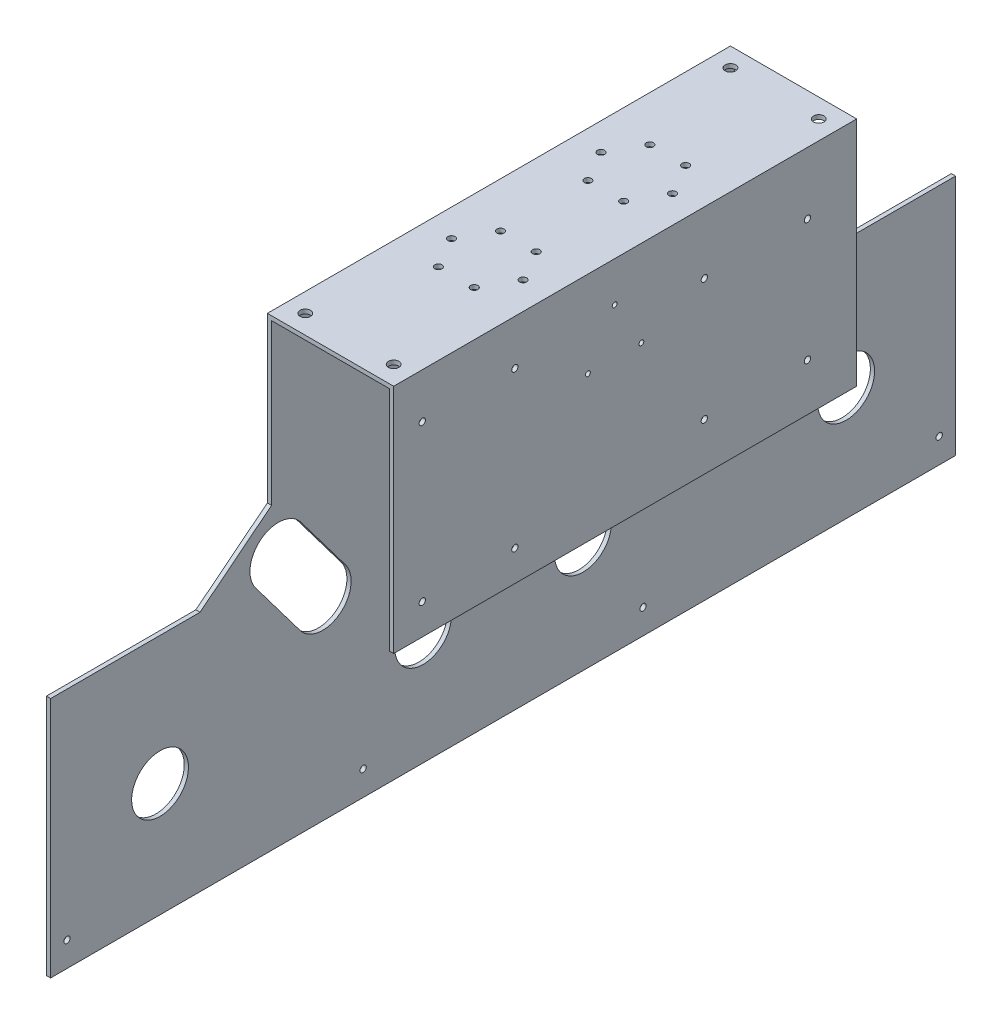
SolidWorks part; units mm, degrees
ref_plane "Front Plane" through (0, 0, 0) normal (0, 0, 1) x (1, 0, 0)
ref_plane "Top Plane" through (0, 0, 0) normal (0, 1, 0) x (1, 0, 0)
ref_plane "Right Plane" through (0, 0, 0) normal (1, 0, 0) x (0, 0, -1)
sketch "Sketch1" plane through (0, 0, 0) normal (0, 0, 1) x (1, 0, 0)
  line L1 (-58, -2) -> (-2, -2)
  line L2 (-2, -2) -> (-2, -110)
  line L6 (0, -110) -> (0, 0)
  line L7 (0, 0) -> (-60, 0)
  line L8 (-2, -110) -> (0, -110)
  line L9 (-60, 0) -> (-60, -220)
  line L10 (-60, -220) -> (-58, -220)
  line L11 (-58, -220) -> (-58, -2)
  dimension "D1" = 60
  dimension "D2" = 2
  dimension "D3" = 2
  dimension "D4" = 110
  dimension "D5" = 220
  dimension "D6" = 2
extrude "Boss-Extrude1" add sketch "Sketch1" along normal blind 220
sketch "Sketch2" plane through (0, 0, 0) normal (0, 1, 0) x (1, 0, 0)
  line L0 (-60, -110) -> (0, -110) construction
  line L2 (-30, -128.5) -> (-30, -162.5) construction
  line L3 (-47, -74.5) -> (-30, -74.5) construction
  line L4 (-47, -145.5) -> (-30, -145.5) construction
  line L5 (-30, -74.5) -> (-47, -74.5) construction
  line L6 (-30, -145.5) -> (-47, -145.5) construction
  line L7 (-30, -74.5) -> (-30, -91.5) construction
  line L9 (-30, -74.5) -> (-42.5, -62.5) construction
  line L10 (-60, -220) -> (-60, 0) construction
  line L11 (0, -220) -> (0, 0) construction
  circle A0 centre (-30, -74.5) radius 17 construction
  circle A1 centre (-30, -145.5) radius 17 construction
  circle A2 centre (-47, -74.5) radius 1.7
  circle A3 centre (-47, -74.5) radius 3
  circle A4 centre (-47, -145.5) radius 1.7
  circle A5 centre (-47, -145.5) radius 3
  circle A6 centre (-38.5, -59.7776) radius 3
  circle A7 centre (-38.5, -59.7776) radius 1.7
  circle A8 centre (-21.5, -59.7776) radius 3
  circle A9 centre (-21.5, -59.7776) radius 1.7
  circle A10 centre (-13, -74.5) radius 3
  circle A11 centre (-13, -74.5) radius 1.7
  circle A12 centre (-21.5, -89.2224) radius 3
  circle A13 centre (-21.5, -89.2224) radius 1.7
  circle A14 centre (-38.5, -89.2224) radius 3
  circle A15 centre (-38.5, -89.2224) radius 1.7
  circle A16 centre (-38.5, -130.7776) radius 1.7
  circle A17 centre (-38.5, -130.7776) radius 3
  circle A18 centre (-21.5, -130.7776) radius 1.7
  circle A19 centre (-21.5, -130.7776) radius 3
  circle A20 centre (-13, -145.5) radius 1.7
  circle A21 centre (-13, -145.5) radius 3
  circle A22 centre (-21.5, -160.2224) radius 1.7
  circle A23 centre (-21.5, -160.2224) radius 3
  circle A24 centre (-38.5, -160.2224) radius 1.7
  circle A25 centre (-38.5, -160.2224) radius 3
  dimension "D2" = 34
  dimension "D3" = 6
  dimension "D4" = 3.4
  dimension "D5" = 3.4
  dimension "D6" = 6
  dimension "D1" = 71
  dimension "D9" = 17
  dimension "D11" = 17
  dimension "D8" = 6
  dimension "D10" = 6
extrude "Cut-Extrude2" cut sketch "Sketch2" against normal up to surface (2 mm away) contours A7 | A9 | A11 | A13 | A15 | A2 | A16 | A4 | A24 | A22 | A20 | A18 up to face at (-30, -2, 110)
sketch "Sketch3" plane through (0, 0, 0) normal (1, 0, 0) x (0, 0, -1)
  line L0 (-127.7, -40.9985) -> (-102.3, -40.9985) construction
  line L1 (-102.3, -40.9985) -> (-115, -19.0015) construction
  line L2 (-115, -19.0015) -> (-127.7, -40.9985) construction
  line L3 (-127.7, -40.9985) -> (-115, -40.9985) construction
  line L4 (-115, -40.9985) -> (-115, -19.0015) construction
  line L13 (-121.35, -30) -> (-108.65, -30) construction
  circle A0 centre (-115, -19.0015) radius 1.15
  circle A1 centre (-127.7, -40.9985) radius 1.15
  circle A2 centre (-102.3, -40.9985) radius 1.15
  dimension "D1" = 2.3
  dimension "D2" = 2.3
  dimension "D3" = 2.3
  dimension "D4" = 25.4
  dimension "D5" = 25.4
  dimension "D6" = 25.4
  dimension "D7" = 115
  dimension "D8" = 30
extrude "Cut-Extrude4" cut sketch "Sketch3" against normal blind 10
sketch "Sketch4" plane through (0, 0, 0) normal (1, 0, 0) x (0, 0, -1)
  line L0 (-206.3978, -21.4333) -> (-162.3978, -21.4333) construction
  line L1 (-162.3978, -21.4333) -> (-162.3978, -95.4333) construction
  line L2 (-162.3978, -95.4333) -> (-206.3978, -95.4333) construction
  line L3 (-206.3978, -95.4333) -> (-206.3978, -21.4333) construction
  line L4 (-72.3978, -29.4333) -> (-23.3978, -29.4333) construction
  line L5 (-23.3978, -29.4333) -> (-23.3978, -87.4333) construction
  line L6 (-72.3978, -87.4333) -> (-72.3978, -29.4333) construction
  line L7 (-72.3978, -87.4333) -> (-23.3978, -87.4333) construction
  circle A0 centre (-206.3978, -21.4333) radius 1.5
  circle A1 centre (-162.3978, -21.4333) radius 1.5
  circle A2 centre (-206.3978, -95.4333) radius 1.5
  circle A3 centre (-162.3978, -95.4333) radius 1.5
  circle A4 centre (-72.3978, -29.4333) radius 1.5
  circle A5 centre (-23.3978, -29.4333) radius 1.5
  circle A6 centre (-72.3978, -87.4333) radius 1.5
  circle A7 centre (-23.3978, -87.4333) radius 1.5
  dimension "D1" = 3
  dimension "D2" = 3
  dimension "D3" = 3
  dimension "D4" = 3
  dimension "D9" = 3
  dimension "D10" = 3
  dimension "D11" = 3
  dimension "D12" = 3
  dimension "D5" = 74
  dimension "D6" = 44
  dimension "D7" = 40
  dimension "D8" = 37
  dimension "D13" = 58
  dimension "D14" = 49
  dimension "D15" = 29
  dimension "D16" = 50
extrude "Cut-Extrude5" cut sketch "Sketch4" against normal blind 10
sketch "Sketch6" plane through (-60, 0, 0) normal (-1, 0, 0) x (0, 0, 1)
  line L0 (0, -78) -> (-34, -105)
  line L1 (0, 0) -> (0, -220) construction
  line L2 (-34, -105) -> (-105, -105)
  line L3 (-105, -105) -> (-105, -220)
  line L4 (-105, -220) -> (0, -220)
  line L5 (110, 0) -> (110, -220) construction
  line L6 (220, 0) -> (0, 0) construction
  line L7 (220, -220) -> (0, -220) construction
  line L8 (0, -78) -> (0, -220)
  line L9 (220, -78) -> (220, -220)
  line L10 (325, -220) -> (220, -220)
  line L11 (325, -105) -> (325, -220)
  line L12 (254, -105) -> (325, -105)
  line L13 (220, -78) -> (254, -105)
  dimension "D1" = 34
  dimension "D2" = 105
  dimension "D3" = 27
  dimension "D4" = 105
extrude "Boss-Extrude2" add sketch "Sketch6" against normal blind 2
sketch "Sketch8" plane through (-60, 0, 0) normal (-1, 0, 0) x (0, 0, 1)
  line L0 (-7.5632, -108.249) -> (13.5004, -136.2012)
  line L1 (14, -92) -> (35.0635, -119.9522)
  line L2 (3.2184, -100.1245) -> (24.2819, -128.0767) construction
  line L3 (-34, -105) -> (-105, -105) construction
  line L4 (-105, -105) -> (-105, -220) construction
  line L5 (325, -220) -> (-105, -220) construction
  line L6 (110, 0) -> (110, -220) construction
  line L7 (220, 0) -> (0, 0) construction
  line L8 (-53, -166) -> (72, -166) construction
  line L9 (206, -92) -> (184.9365, -119.9522)
  line L10 (227.5632, -108.249) -> (206.4996, -136.2012)
  line L11 (-97.2, -208.2) -> (43.5, -208.2) construction
  arc A0 (14, -92) -> (-7.5632, -108.249) centre (3.2184, -100.1245) ccw
  arc A1 (13.5004, -136.2012) -> (35.0635, -119.9522) centre (24.2819, -128.0767) ccw
  circle A2 centre (-53, -166) radius 13.5
  circle A3 centre (72, -166) radius 13.5
  circle A4 centre (148, -166) radius 13.5
  arc A5 (206, -92) -> (227.5632, -108.249) centre (216.7816, -100.1245) cw
  arc A6 (206.4996, -136.2012) -> (184.9365, -119.9522) centre (195.7181, -128.0767) cw
  circle A7 centre (273, -166) radius 13.5
  circle A8 centre (-97.2, -208.2) radius 1.5
  circle A9 centre (43.5, -208.2) radius 1.5
  circle A10 centre (176.5, -208.2) radius 1.5
  circle A11 centre (317.2, -208.2) radius 1.5
  circle A12 centre (71.99, -66.8) radius 13.5
  circle A13 centre (148.01, -66.8) radius 13.5
  dimension "D1" = 27
  dimension "D2" = 27
  dimension "D4" = 14
  dimension "D7" = 27
  dimension "D8" = 27
  dimension "D12" = 3
  dimension "D13" = 3
  dimension "D17" = 27
  dimension "D3" = 35
  dimension "D5" = 14
  dimension "D6" = 53
  dimension "D9" = 52
  dimension "D10" = 54
  dimension "D11" = 38
  dimension "D14" = 7.8
  dimension "D15" = 148.5
  dimension "D16" = 11.8
  dimension "D18" = 38.01
  dimension "D19" = 66.8
extrude "Cut-Extrude6" cut sketch "Sketch8" against normal blind 2
sketch "Sketch9" plane through (0, 0, 0) normal (0, 1, 0) x (1, 0, 0)
  line L0 (-60, -220) -> (-60, 0) construction
  line L1 (0, 0) -> (-60, 0) construction
  line L2 (0, -220) -> (0, 0) construction
  line L3 (-60, -110) -> (0, -110) construction
  circle A0 centre (-51, -9) radius 2.5
  circle A1 centre (-9, -9) radius 2.5
  circle A3 centre (-9, -211) radius 2.5
  circle A4 centre (-51, -211) radius 2.5
  dimension "D1" = 5
  dimension "D2" = 5
  dimension "D3" = 9
  dimension "D4" = 9
  dimension "D5" = 9
  dimension "D6" = 9
extrude "Cut-Extrude7" cut sketch "Sketch9" against normal blind 10
